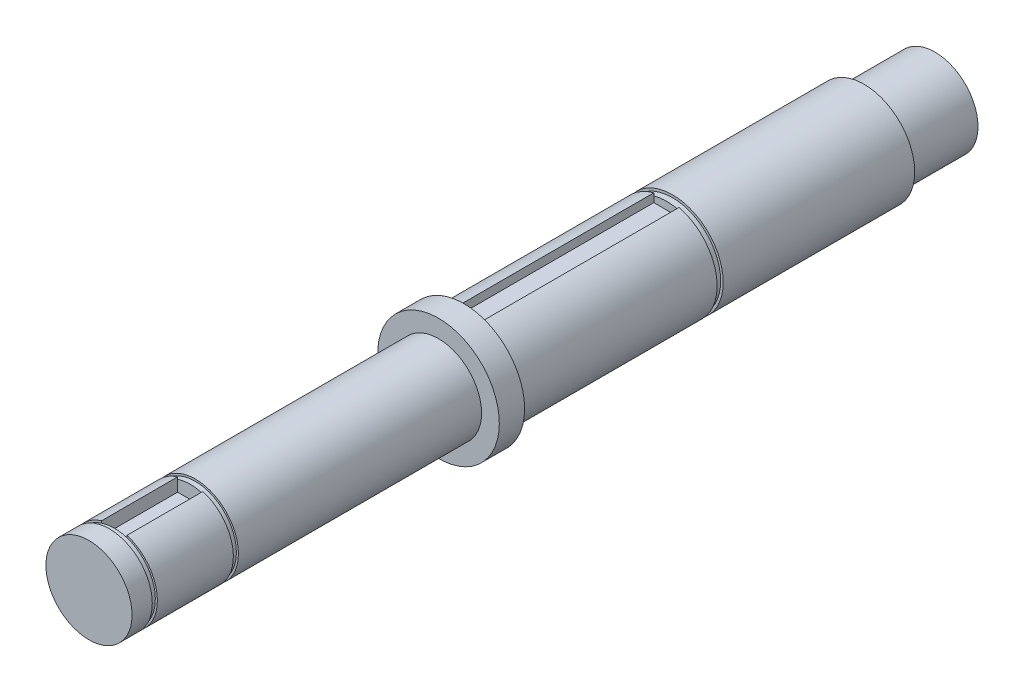
SolidWorks part; units mm, degrees
ref_plane "Front Plane" through (0, 0, 0) normal (0, 0, 1) x (1, 0, 0)
ref_plane "Top Plane" through (0, 0, 0) normal (0, 1, 0) x (1, 0, 0)
ref_plane "Right Plane" through (0, 0, 0) normal (1, 0, 0) x (0, 0, -1)
sketch "Sketch2" plane through (0, 0, 0) normal (1, 0, 0) x (0, 0, -1)
  line L0 (0, 0) -> (121.9703, 0) construction
  line L1 (0, 0) -> (0, 8.5)
  line L2 (0, 8.5) -> (14, 8.5)
  line L3 (14, 8.5) -> (14, 12)
  line L4 (14, 12) -> (19, 12)
  line L5 (19, 12) -> (19, 10)
  line L6 (19, 10) -> (98, 10)
  line L7 (98, 10) -> (98, 8.5)
  line L8 (98, 8.5) -> (112, 8.5)
  line L9 (112, 8.5) -> (112, 0)
  line L10 (112, 0) -> (0, 0)
  dimension "D1" = 84
  dimension "D2" = 14
  dimension "D3" = 14
  dimension "D4" = 12
  dimension "D5" = 8.5
  dimension "D6" = 8.5
  dimension "D7" = 10
  dimension "D8" = 5
revolve "Revolve1" add sketch "Sketch2" angle 360 about L0
sketch "Sketch3" plane through (0, 0, 0) normal (0, 0, 1) x (1, 0, 0)
  line L0 (2.5, 8) -> (-2.5, 8)
  line L2 (2.5, 8) -> (2.5, 16)
  line L4 (2.5, 16) -> (-2.5, 16)
  line L5 (-2.5, 8) -> (-2.5, 16)
  point P1 (0, 8)
  dimension "D1" = 5
  dimension "D2" = 8
  dimension "D3" = 8
extrude "Cut-Extrude1" cut sketch "Sketch3" against normal blind 40 from offset 19 offset against normal yes
sketch "Sketch4" plane through (0, 0, -59) normal (0, 0, 1) x (1, 0, 0)
  circle A0 centre (0, 0) radius 9.5
  circle A1 centre (0, 0) radius 12.5
  dimension "D1" = 3
  dimension "D2" = 19
extrude "Cut-Extrude2" cut sketch "Sketch4" against normal blind 1.2
sketch "Sketch5" plane through (0, 0, 0) normal (0, 0, 1) x (1, 0, 0)
  circle A0 centre (0, 0) radius 8.5
  dimension "D1" = 17
extrude "Boss-Extrude1" add sketch "Sketch5" along normal blind 50
sketch "Sketch8" plane through (0, 0, 50) normal (0, 0, 1) x (1, 0, 0)
  line L1 (-2.5, 8.5) -> (2.5, 8.5)
  line L2 (-2.5, 8.5) -> (-2.5, 5.5)
  line L3 (-2.5, 5.5) -> (2.5, 5.5)
  line L4 (2.5, 8.5) -> (2.5, 5.5)
  circle A1 centre (0, 0) radius 8.5 construction
  point P4 (0, 8.5)
  point P6 (0, 5.5)
  dimension "D1" = 5
  dimension "D2" = 3
extrude "Cut-Extrude3" cut sketch "Sketch8" against normal blind 15
sketch "Sketch9" plane through (0, 0, 50) normal (0, 0, 1) x (1, 0, 0)
  circle A0 centre (0, 0) radius 8.5
  dimension "D1" = 17
extrude "Boss-Extrude2" add sketch "Sketch9" along normal blind 5
sketch "Sketch10" plane through (0, 0, 50) normal (0, 0, -1) x (-1, 0, 0)
  circle A0 centre (0, 0) radius 8.1
  circle A1 centre (0, 0) radius 10.1
  dimension "D1" = 16.2
  dimension "D2" = 2
extrude "Cut-Extrude4" cut sketch "Sketch10" against normal blind 1
sketch "Sketch11" plane through (0, 0, 35) normal (0, 0, 1) x (1, 0, 0)
  circle A0 centre (0, 0) radius 8.1
  circle A1 centre (0, 0) radius 10.1
  dimension "D1" = 2
  dimension "D2" = 16.2
extrude "Cut-Extrude5" cut sketch "Sketch11" against normal blind 1
